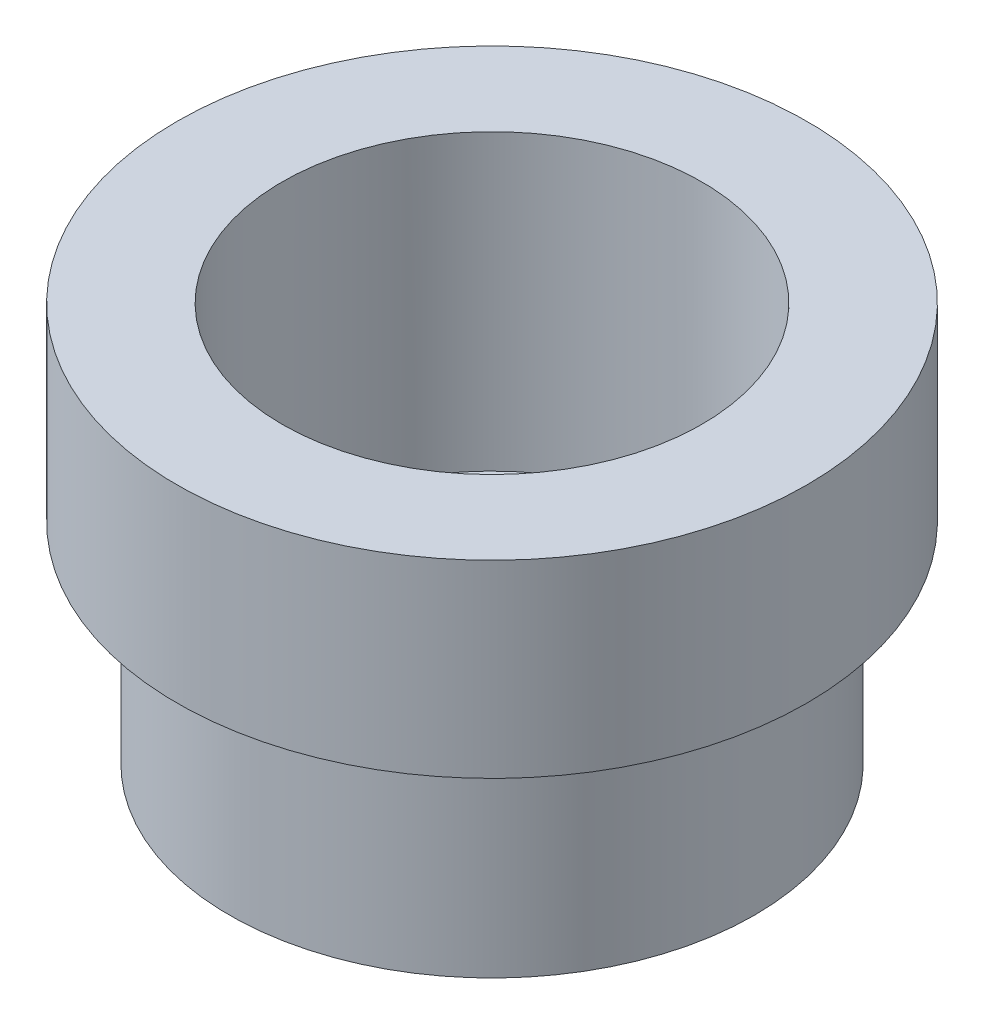
SolidWorks part; units mm, degrees
material "1060 Alloy"
ref_plane "Front" through (0, 0, 0) normal (0, 0, 1) x (1, 0, 0)
ref_plane "Top" through (0, 0, 0) normal (0, 1, 0) x (1, 0, 0)
ref_plane "Right" through (0, 0, 0) normal (1, 0, 0) x (0, 0, -1)
sketch "Sketch1" plane through (0, 0, 0) normal (0, 0, 1) x (1, 0, 0)
  line L0 (0, 0) -> (25, 0)
  line L1 (25, 0) -> (25, 20)
  line L2 (25, 20) -> (30, 20)
  line L3 (30, 20) -> (30, 38)
  line L6 (30, 38) -> (0, 38)
  line L7 (0, 38) -> (0, 0)
  dimension "D1" = 18
  dimension "D2" = 20
  dimension "D3" = 30
  dimension "D4" = 25
revolve "Revolve1" add sketch "Sketch1" angle 360 about L7
sketch "Sketch3" plane through (0, 38, 0) normal (0, 1, 0) x (1, 0, 0)
  circle A0 centre (0, 0) radius 10
  dimension "D1" = 20
extrude "bore through" cut sketch "Sketch3" against normal through all
sketch "Sketch5" plane through (0, 38, 0) normal (0, 1, 0) x (1, 0, 0)
  circle A0 centre (0, 0) radius 20
  dimension "D1" = 40
extrude "center cavity" cut sketch "Sketch5" against normal offset from surface (28 mm away) 10 up to face at (0, 0, 10)
sketch "m4 pattern alignment" plane through (0, 10, 0) normal (0, 1, 0) x (1, 0, 0)
  circle A0 centre (0, 0) radius 15 construction
  circle A1 centre (0, 15) radius 2.15
  point P3 (0, 15)
  point P4 (12.9904, 7.5)
  point P7 (12.9904, -7.5)
  point P8 (0, -15)
  point P9 (-12.9904, -7.5)
  point P10 (-12.9904, 7.5)
  point P11 (0, 0)
  dimension "D1" = 30
  dimension "D3" = 4.3
  dimension "D2" = 6
extrude "Cut-Extrude1" cut sketch "m4 pattern alignment" against normal through all
pattern_circular "CirPattern1" count 6 over 360 about axis through (0, 0, 0) along (0, 1, 0) of "Cut-Extrude1"
sketch "Sketch7" plane through (0, 10, 0) normal (0, 1, 0) x (1, 0, 0)
  circle A0 centre (0, 15) radius 4
extrude "Cut-Extrude2" cut sketch "Sketch7" against normal blind 4
pattern_circular "CirPattern2" count 6 over 360 about axis through (0, 0, 0) along (0, 1, 0) of "Cut-Extrude2"
sketch "Sketch8" plane through (0, 0, 0) normal (0, -1, 0) x (1, 0, 0)
  line L1 (0, 0) -> (-31.496, 0) construction
  line L2 (0, 0) -> (0, -31.496) construction
  line L3 (0, -31.496) -> (-31.496, -31.496) construction
  line L4 (-31.496, 0) -> (-31.496, -31.496) construction
  dimension "D1" = 31.496
  dimension "D2" = 31.496
equation "\"D1\"= \"motor mount plate thickness\""
equation "\"coupler motor shaft hole ID\"= 8mm"
equation "\"coupler OD\"= 17mm"
equation "\"coupler length\"= 25mm"
equation "\"square plate bolt pattern diameter\"= 3.5in"
equation "\"motor mount m4 screw hole diameter\"= 4mm"
equation "\"motor mount m4 head diameter\"= 7.25mm"
equation "\"motor mount m4 head depth\"= 4mm"
equation "\"motor mount plate thickness\"= 8mm + \"motor mount m4 head depth\""
equation "\"motor shaft pride\"= 32mm"
equation "\"motor mount m4 pattern diamater\" = 30mm"
equation "\"motor OD\" = 64mm"
equation "\"square plate bolt bore\" = \"m8 clearance\""
equation "\"square plate bolt head diameter\" = 13.5mm"
equation "\"motor to bearing plate distance\" = \"motor shaft pride\" + 2mm +\"coupler length\"/2"
equation "\"motor mount center bore\"= \"coupler OD\"+ 4mm"
equation "\"motor mount post radius\"= ( 3 * \"square plate bolt bore\" ) / 2"
equation "\"motor shaft diameter\"= 8mm"
equation "\"D1\"= 20mm"
equation "\"z\" = 8\t\t\t\t'number of blades"
equation "\"de\" = 0.43in\t\t\t'entrance eye diameter"
equation "\"de_length\" = 4mm\t\t'entrance eye consistent length"
equation "\"d_exit\" = 0.18in \t\t'throat aka d1"
equation "\"d2\" = 2.1in \t\t\t'outer diameter of the impeller"
equation "\"b2\" = .2in\t\t\t'tip height from disc surface at d2; slightly higher than d_exit"
equation "\"theta\" = 12\t\t\t'angle of blades from inner to outer "
equation "\"ae\" = 3.14*(\"de\"^2)/4\t\t'entrance eye area'"
equation "\"ce\" = 3.14*\"de\"\t\t'entrance eye circumference"
equation "\"av_ratio\" = .325\t\t'ratio of av/ae at N_s of 470, range is .275 to .375, .325 ideal. High ratio means bigger area means smaller blades"
equation "\"av\" = \"ae\"*\"av_ratio\"\t\t'area between just two blades"
equation "\"min blade thickness\" = .15in"
equation "\"diffuser cartridge OD\" =.75in"
equation "\"diffuser flange bolt pattern diameter\" = 1.4in"
equation "\"bearing OD\" = 30mm"
equation "\"bearing ID\"= 10mm"
equation "\"bearing depth\"= 9mm"
equation "\"bearing outer race thickness\"= 1mm"
equation "\"bearing inner race thickness\"= 1mm"
equation "\"bearing bore\" = \"bearing depth\" + 1mm"
equation "\"lower seal OD\" = .917in\t\t'this is https://www.mcmaster.com/#9281k121/=174001b"
equation "\"lower seal ID\"= .375in"
equation "\"lower seal depth\" = .625in + .218in"
equation "\"lower seal bore\" = \"lower seal depth\" + 1mm"
equation "\"upper seal OD\" = 1.125in\t'this is https://www.mcmaster.com/#5154t33/=173zuau, needs to be visually inspected before machining!"
equation "\"upper seal ID\"= 0.625in"
equation "\"upper seal depth\"= .25in\t'aka height; these values need to be confirmed by inspection!! We may want to compress the height."
equation "\"upper seal bore\" = \"upper seal depth\" + 1mm"
equation "\"big o-ring thickness\" = .139in"
equation "\"big o-ring OD\" = 2.734in"
equation "\"big o-ring ID\" = 3.012in"
equation "\"big o-ring groove depth\" = \"big o-ring thickness\"*4/5"
equation "\"impeller upper clearance\"= .5mm"
equation "\"impeller horizontal clearance\"= (\"d2\"*1.15 - \"d2\")/2 \t\t'clearance based on D2-D3 ratio for circular volute, ranges 1.15 to 1.2"
equation "\"impeller bottom clearance\"= .5mm"
equation "\"impeller base thickness\"= 2mm"
equation "\"impeller dowel diameter\" = 2mm"
equation "\"impeller bolt head depth\" = 4mm"
equation "\"impeller bolt stop depth\" = 3mm"
equation "\"impeller shaft bore depth\" = 12mm"
equation "\"impeller shaft bore\" = 8mm"
equation "\"impeller boss depth\" = \"impeller shaft bore depth\"+\"impeller bolt stop depth\"+\"impeller bolt head depth\"-\"impeller base thickness\""
equation "\"impeller boss diameter\" = \"upper seal ID\""
equation "\"impeller dowel length\" = 2mm*2 + \"impeller shaft bore\""
equation "\"square plate bolt head depth\" = 8mm"
equation "\"bearing plate stop ID\" = \"bearing OD\" - 4mm"
equation "\"bearing plate stop depth\" = 3mm"
equation "\"lower seal plate lip depth\" = 2mm"
equation "\"lower seal plate lip ID\" = \"lower seal OD\" - 3mm"
equation "\"lower seal plate thickness\" = \"lower seal plate lip depth\" + \"lower seal bore\""
equation "\"shaft coupler section diameter\" = 8mm"
equation "\"shaft coupler section length\" = \"motor to bearing plate distance\" - \"motor shaft pride\" - 2mm"
equation "\"shaft bearing section diameter\" = \"bearing ID\""
equation "\"shaft bearing section length\" = \"bearing plate stop depth\" + \"bearing depth\""
equation "\"shaft bearing stop diameter\" = \"bearing ID\" + 4mm"
equation "\"shaft bearing stop length\" = 3mm"
equation "\"shaft lower seal section diameter\" = \"lower seal ID\""
equation "\"shaft lower seal section length\" = \"lower seal plate thickness\" + 1mm"
equation "\"shaft impeller section diameter\" = \"impeller shaft bore\""
equation "\"upper seal plate lip ID\" = \"upper seal OD\" - 3mm"
equation "\"upper seal plate riser\" = 6.59mm \t\t'this number needs to be read from the housing file"
equation "\"upper seal plate pressure hole diameter\" = .125in\t'this is 1/8 drill "
equation "\"upper seal plate pressure tap diameter\" = .328125in \t'this is 21/64 drill for a 1/8 ANPT tap"
equation "\"upper seal plate pressure tap grip\" = 5mm\t\t'this is the area around the tap so it doesn't crack"
equation "\"upper seal plate pressure tap depth\" = 12mm"
equation "\"impeller cavity diameter\"= 2 * \"impeller horizontal clearance\" + \"d2\" \t\t\t\t\t\t\t\t\t'called D3 analytically"
equation "\"impeller cavity outer height\"= \"impeller bottom clearance\" + \"impeller upper clearance\" + \"impeller base thickness\" + \"b2\" \t\t'this is height at impeller diameter d2, not at d3"
equation "\"impeller housing diameter\" = 4.5in"
equation "\"impeller housing bolt count\" = 8"
equation "\"impeller housing bolt pattern diameter\" = 3.5in"
equation "\"impeller housing threaded inlet diameter\" = 0.71875in \t'this is the 23/32 drill size for 1/2 NPT fitting https://www.mcmaster.com/#50715k269/=176pljy"
equation "\"impeller housing threaded inlet depth\"= .6in"
equation "\"impeller housing exit threaded diameter\"= 0.515625in \t\t'this is the 33/64 drill size for 9/16-18 fitting, expecting swagelok SS-8FK0-1-6STH fitting"
equation "\"impeller housing exit threaded depth\"= 10mm"
equation "\"impeller housing diffuser conical angle\"=10"
equation "\"impeller housing diffuser tangent angle\"=5"
equation "\"impeller housing diffuser final diameter\" = .38in\t\t'aka d2'"
equation "\"impeller housing outlet grip\" = 5mm"
equation "\"end mill size\" = 0.375in\t'for 3/8 endmill"
equation "\"m4 clearance\" = 0.171875in \t'this is 11/64 bit for 4.36mm"
equation "\"m4 tap\" = 0.125in\t\t'this is 1/8 bit for 3.17mm"
equation "\"m4 head bore diameter\" = 7.5mm"
equation "\"m4 head bore depth\" = 5mm\t'actual is ~4mm"
equation "\"m6 clearance\" = 0.234375in\t'this is 15/64 bit = 5.95mm, could use 6mm bit, B bit for 6.04mm or 1/4 bit for 6.35mm"
equation "\"m6 tap\" = 5mm\t\t\t'5mm is appropriate, could use 13/64 or #5,6,7"
equation "\"m6 head bore diameter\" = 11mm\t\t"
equation "\"m6 head bore depth\" = 7mm\t'actual is 6mm"
equation "\"m8 clearance\" = 0.3125in\t'this is 5/16in for 7.93mm, could use 8mm, O,P, or 21/64"
equation "\"m8 tap\" = 0.265625in\t\t'this is 17/64 for 6.746875mm"
equation "\"m8 head bore diameter\" = 14mm"
equation "\"m8 head bore depth\" = 9mm\t'actual is 8mm"
